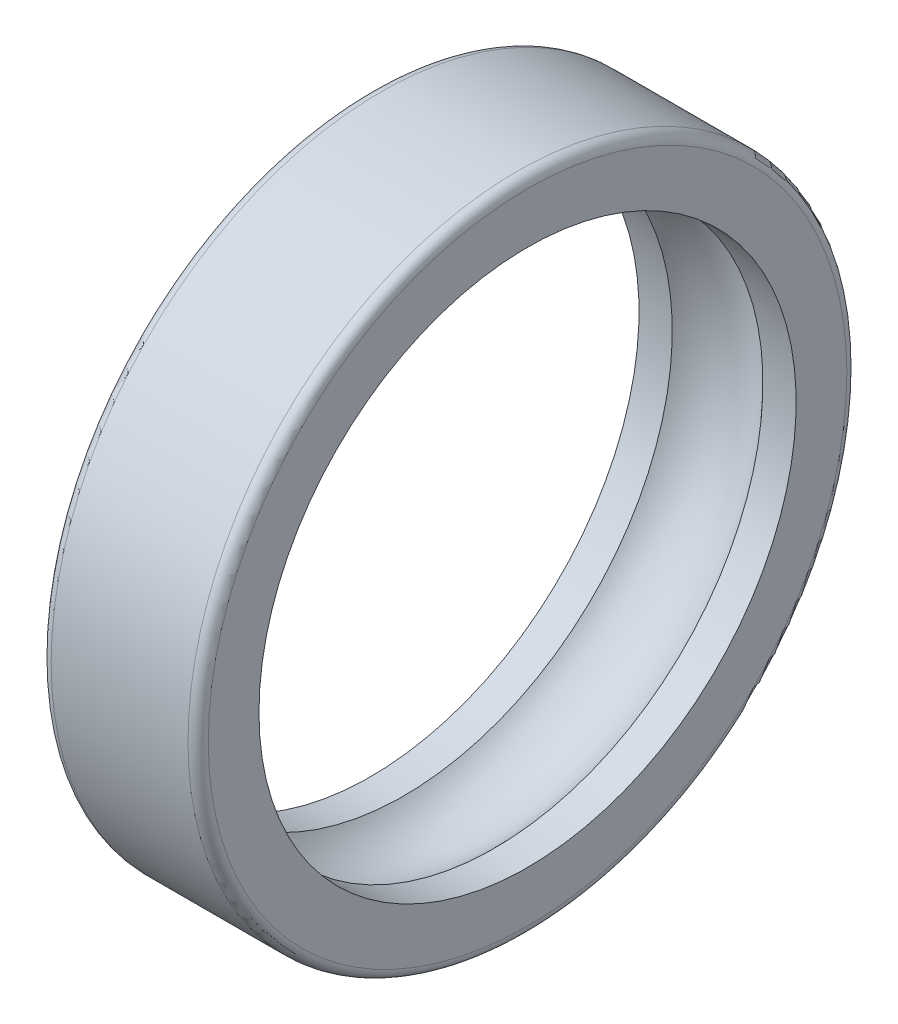
SolidWorks part; units mm, degrees
ref_plane "前视基准面" through (0, 0, 0) normal (0, 0, 1) x (1, 0, 0)
ref_plane "上视基准面" through (0, 0, 0) normal (0, 1, 0) x (1, 0, 0)
ref_plane "右视基准面" through (0, 0, 0) normal (1, 0, 0) x (0, 0, -1)
sketch "草图1" plane through (0, 0, 0) normal (0, 0, 1) x (1, 0, 0)
  line L1 (0, 0) -> (26.5846, 0) construction
  line L2 (8.9443, 53) -> (15.5, 53)
  line L3 (-15.5, 65) -> (15.5, 65)
  line L4 (-15.5, 65) -> (-15.5, 53)
  line L5 (-15.5, 53) -> (-8.9443, 53)
  line L6 (15.5, 65) -> (15.5, 53)
  line L7 (-15.5, 65) -> (15.5, 53) construction
  line L8 (-15.5, 53) -> (15.5, 65) construction
  line L9 (0, 57) -> (0, 72.0508) construction
  arc A0 (-8.9443, 53) -> (8.9443, 53) centre (0, 45) cw
  point P3 (0, 59)
  dimension "D5" = 12
  dimension "D1" = 12
  dimension "D2" = 31
  dimension "D3" = 65
  dimension "D4" = 8
revolve "旋转1" add sketch "草图1" angle 360 about L1
fillet "圆角1" radius 2 2 edges at (-15.5, 0, 65) (15.5, 0, 65)
